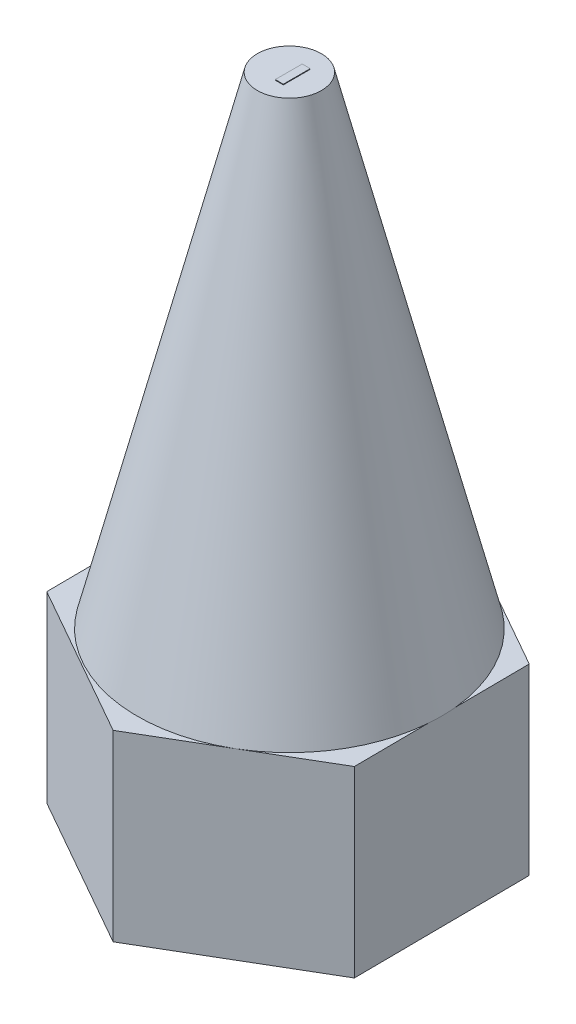
SolidWorks part; units mm, degrees
material "ABS"
ref_plane "Alzado" through (0, 0, 0) normal (0, 0, 1) x (1, 0, 0)
ref_plane "Planta" through (0, 0, 0) normal (0, 1, 0) x (1, 0, 0)
ref_plane "Vista lateral" through (0, 0, 0) normal (1, 0, 0) x (0, 0, -1)
sketch "Croquis1" plane through (0, 0, 0) normal (0, 1, 0) x (1, 0, 0)
  line L1 (12.5555, -7.1199) -> (12.4438, 7.3134)
  line L2 (12.4438, 7.3134) -> (-0.1117, 14.4333)
  line L3 (-0.1117, 14.4333) -> (-12.5555, 7.1199)
  line L4 (-12.5555, 7.1199) -> (-12.4438, -7.3134)
  line L5 (-12.4438, -7.3134) -> (0.1117, -14.4333)
  line L6 (0.1117, -14.4333) -> (12.5555, -7.1199)
  circle A0 centre (0, 0) radius 12.5 construction
  dimension "D1" = 25
extrude "Saliente-Extruir1" add sketch "Croquis1" along normal blind 15
ref_plane "Plano1" through (0, 15, 0) normal (0, 1, 0) x (1, 0, 0)
sketch "Croquis5" plane through (0, 15, 0) normal (0, 1, 0) x (1, 0, 0)
  circle A0 centre (0, 0) radius 10
  dimension "D1" = 20
sketch "Croquis6" plane through (0, 0, 0) normal (0, 0, 1) x (1, 0, 0)
  line L0 (0.1117, 15) -> (0.1117, 65)
  line L1 (0.1117, 65) -> (12.5555, 15)
  line L3 (12.5555, 15) -> (0.1117, 15)
  dimension "D1" = 50
revolve "Revolución3" add sketch "Croquis6" angle 360 about L0
ref_plane "Plano2" through (-6.3336, 0, -10.7766) normal (-0.5067, 0, -0.8621) x (-0.8621, 0, 0.5067)
sketch "Croquis7" plane through (-6.3336, 0, -10.7766) normal (-0.5067, 0, -0.8621) x (-0.8621, 0, 0.5067)
  line L0 (-7.2169, 0) -> (7.2169, 0) construction
  line L1 (-7.2169, 0) -> (7.2169, 0)
  line L2 (-7.2169, 0) -> (-7.2169, 66.7771)
  line L3 (-7.2169, 66.7771) -> (7.2169, 66.7771)
  line L4 (7.2169, 0) -> (7.2169, 66.7771)
  line L7 (7.2169, 54.4717) -> (7.2169, 52.4257)
  line L10 (-7.2169, 66.7771) -> (7.2169, 66.7771)
  line L11 (-7.2169, 66.7771) -> (-7.2169, 54.4717)
  line L12 (-7.2169, 54.4717) -> (7.2169, 54.4717)
  line L13 (7.2169, 66.7771) -> (7.2169, 54.4717)
extrude "Cortar-Extruir1" cut sketch "Croquis7" against normal through all contours L2 L12 L4 L3
sketch "Croquis8" plane through (0, 0, 0) normal (0, -1, 0) x (-1, 0, 0)
  circle A0 centre (0, 0) radius 1.5
  dimension "D1" = 3
extrude "Cortar-Extruir2" cut sketch "Croquis8" against normal blind 1
sketch "Croquis10" plane through (0, 54.4717, 0) normal (0, 1, 0) x (1, 0, 0)
  line L0 (0.1117, -2.6202) -> (0.1117, 2.6202) construction
  line L2 (0.1117, -1.1544) -> (0.7704, -1.1544)
  line L3 (0.1117, -1.1544) -> (0.1117, 1.0511)
  line L4 (0.1117, 1.0511) -> (0.7704, 1.0511)
  line L5 (0.7704, -1.1544) -> (0.7704, 1.0511)
  circle A0 centre (0.1117, 0) radius 2.6202 construction
extrude "Saliente-Extruir2" add sketch "Croquis10" along normal blind 0.05
